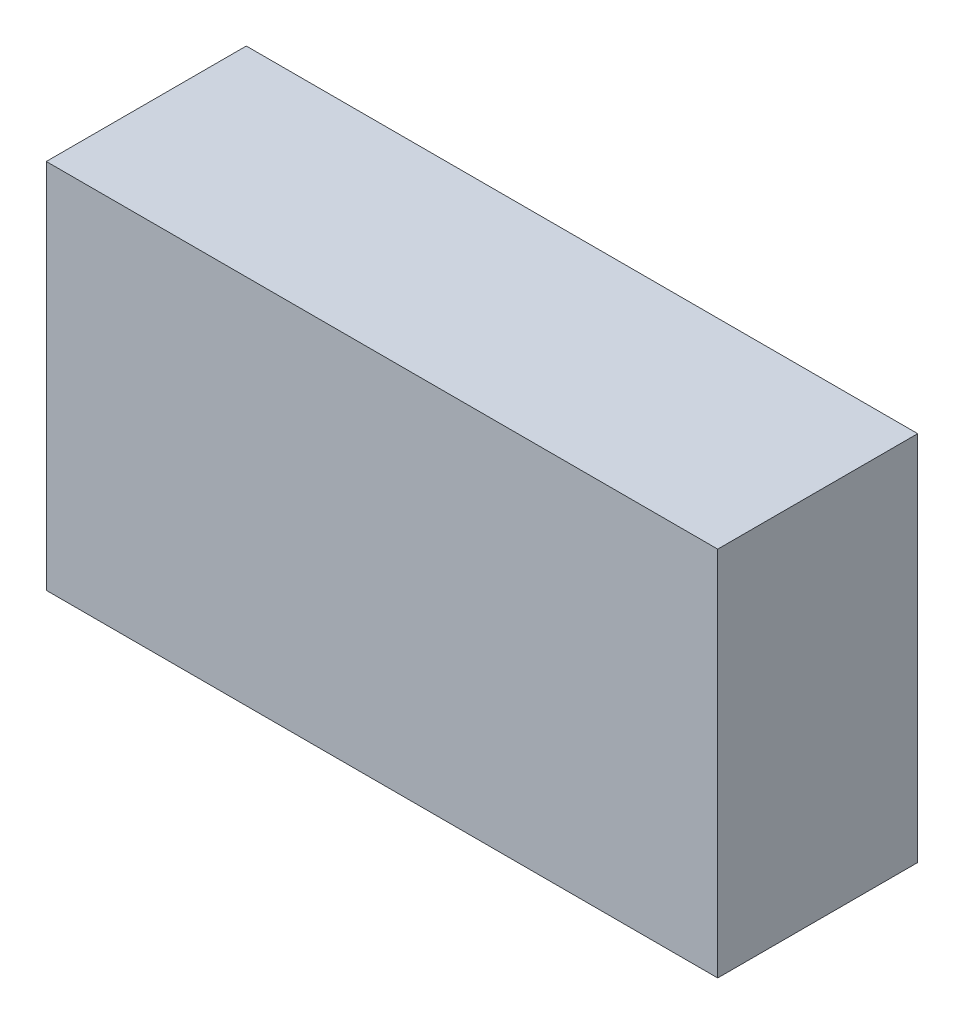
SolidWorks part; units mm, degrees
ref_plane "Front Plane" through (0, 0, 0) normal (0, 0, 1) x (1, 0, 0)
ref_plane "Top Plane" through (0, 0, 0) normal (0, 1, 0) x (1, 0, 0)
ref_plane "Right Plane" through (0, 0, 0) normal (1, 0, 0) x (0, 0, -1)
sketch "Sketch1" plane through (0, 0, 0) normal (0, 0, 1) x (1, 0, 0)
  line L1 (23.5, -13) -> (-23.5, -13)
  line L2 (23.5, -13) -> (23.5, 13)
  line L3 (23.5, 13) -> (-23.5, 13)
  line L4 (-23.5, -13) -> (-23.5, 13)
  line L5 (23.5, -13) -> (-23.5, 13) construction
  line L6 (23.5, 13) -> (-23.5, -13) construction
  point P0 (0, 0)
  dimension "D1" = 26
  dimension "D2" = 47
extrude "Boss-Extrude1" add sketch "Sketch1" along normal blind 14
sketch "Sketch2" plane through (0, 0, 0) normal (0, 0, -1) x (-1, 0, 0)
  text T0 "7.4V\r\n450mAh"
extrude "Boss-Extrude2" add sketch "Sketch2" along normal blind 0.5
